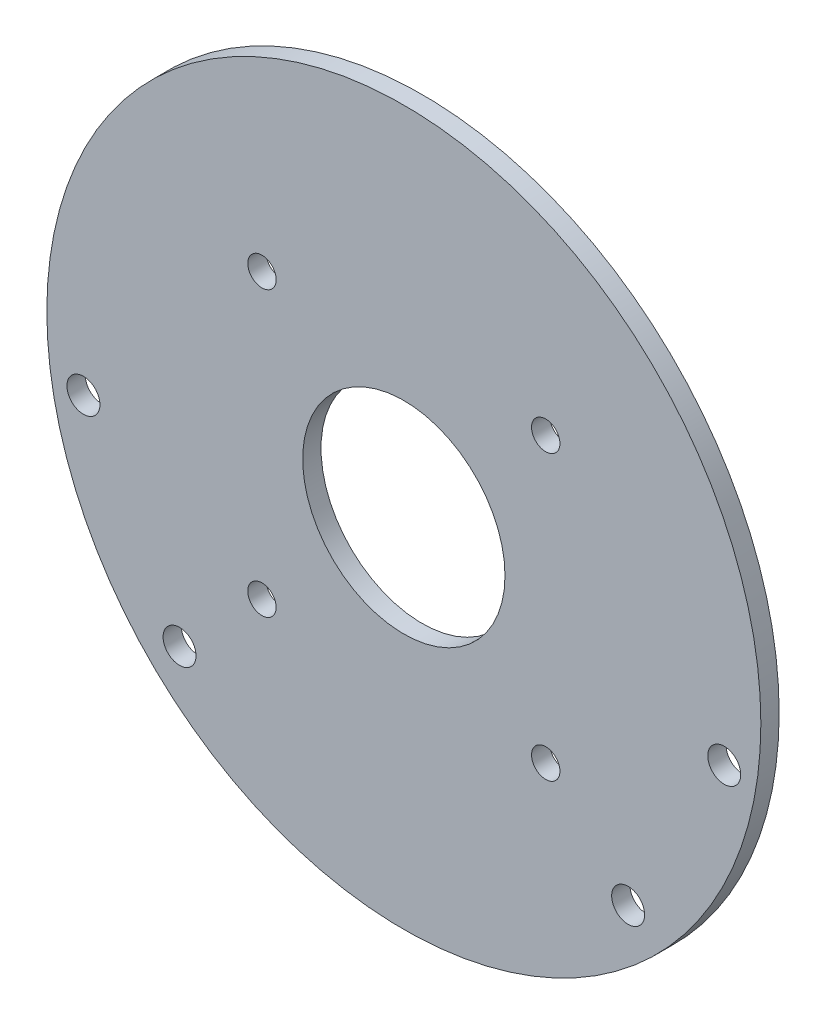
SolidWorks part; units mm, degrees
ref_plane "前视基准面" through (0, 0, 0) normal (0, 0, 1) x (1, 0, 0)
ref_plane "上视基准面" through (0, 0, 0) normal (0, 1, 0) x (1, 0, 0)
ref_plane "右视基准面" through (0, 0, 0) normal (1, 0, 0) x (0, 0, -1)
sketch "草图1" plane through (0, 0, 0) normal (0, 0, 1) x (1, 0, 0)
  line L0 (0, 0) -> (0, 25) construction
  line L1 (0, 0) -> (25, 0) construction
  line L3 (-21, 21) -> (21, 21) construction
  line L4 (-21, 21) -> (-21, -21) construction
  line L5 (-21, -21) -> (21, -21) construction
  line L6 (21, 21) -> (21, -21) construction
  line L7 (-21, 21) -> (21, -21) construction
  line L8 (-21, -21) -> (21, 21) construction
  circle A0 centre (0, 0) radius 39
  circle A1 centre (15.5, -15.5) radius 1.55
  circle A2 centre (-15.5, -15.5) radius 1.55
  circle A3 centre (15.5, 15.5) radius 1.55
  circle A4 centre (-15.5, 15.5) radius 1.55
  circle A5 centre (-21, -21) radius 1.8
  circle A6 centre (-21, 21) radius 1.8
  circle A7 centre (21, 21) radius 1.8
  circle A8 centre (21, -21) radius 1.8
  dimension "D1" = 78
  dimension "D2" = 3.1
  dimension "D7" = 3.6
  dimension "D8" = 3.6
  dimension "D9" = 3.6
  dimension "D10" = 3.6
  dimension "D3" = 15.5
  dimension "D4" = 15.5
  dimension "D5" = 42
  dimension "D6" = 42
extrude "凸台-拉伸1" add sketch "草图1" along normal blind 2 contours A0
sketch "草图3" plane through (0, 0, 2) normal (0, 0, 1) x (1, 0, 0)
  circle A1 centre (-15.5, -15.5) radius 1.55 construction
  circle A3 centre (15.5, -15.5) radius 1.55 construction
  circle A5 centre (15.5, 15.5) radius 1.55 construction
  circle A6 centre (-15.5, 15.5) radius 1.55 construction
  circle A9 centre (-15.5, -15.5) radius 1.55
  circle A11 centre (15.5, -15.5) radius 1.55
  circle A13 centre (15.5, 15.5) radius 1.55
  circle A14 centre (-15.5, 15.5) radius 1.55
extrude "切除-拉伸2" cut sketch "草图3" against normal blind 2
sketch "草图4" plane through (0, 0, 2) normal (0, 0, 1) x (1, 0, 0)
  line L0 (-21, -21) -> (21, 21) construction
  circle A0 centre (0, 0) radius 11.05
  dimension "D1" = 22.1
extrude "切除-拉伸3" cut sketch "草图4" against normal blind 2
sketch "草图6" plane through (0, 0, 2) normal (0, 0, 1) x (1, 0, 0)
  line L0 (0, -200000) -> (0, 200025) construction
  line L1 (0, 33) -> (0, -33) construction
  circle A0 centre (24.5, -24.4591) radius 1.8
  circle A3 centre (-24.5, -24.4591) radius 1.8
  circle A5 centre (35, -5.9591) radius 1.8
  circle A6 centre (-35, -5.9591) radius 1.8
  dimension "D1" = 3.6
  dimension "D3" = 3.6
  dimension "D2" = 24.5
extrude "切除-拉伸4" cut sketch "草图6" against normal blind 10
